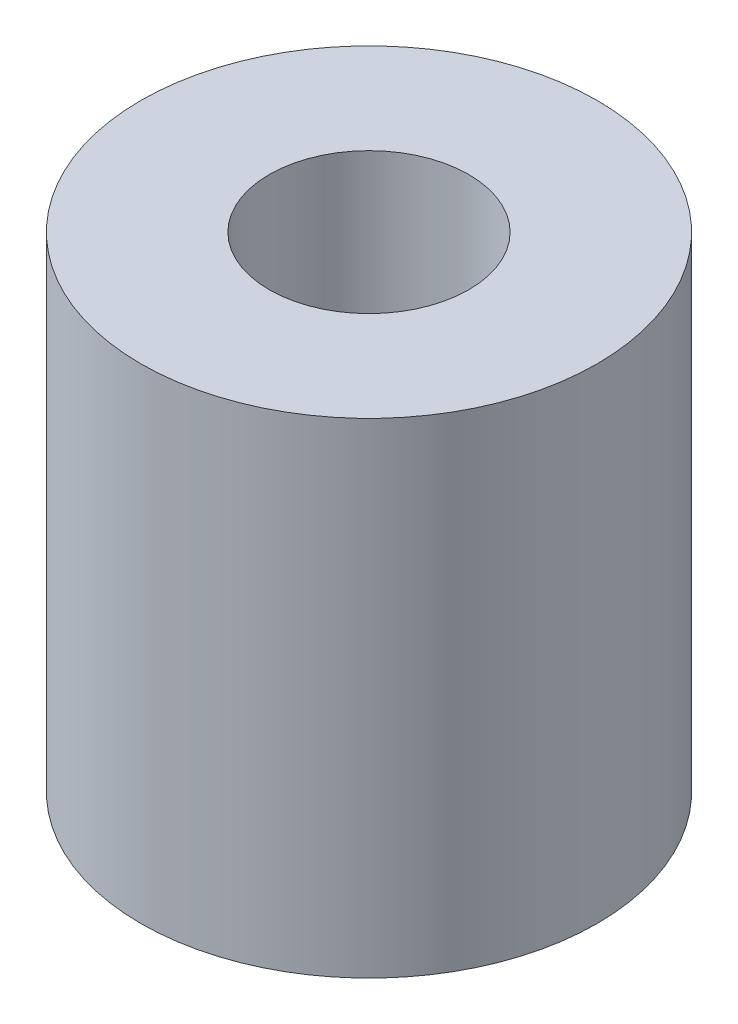
SolidWorks part; units mm, degrees
ref_plane "Спереди" through (0, 0, 0) normal (0, 0, 1) x (1, 0, 0)
ref_plane "Сверху" through (0, 0, 0) normal (0, 1, 0) x (1, 0, 0)
ref_plane "Справа" through (0, 0, 0) normal (1, 0, 0) x (0, 0, -1)
sketch "Эскиз1" plane through (0, 0, 0) normal (0, 1, 0) x (1, 0, 0)
  circle A0 centre (0, 0) radius 4
  circle A1 centre (0, 0) radius 1.75
  dimension "D1" = 8
  dimension "D2" = 3.5
extrude "Бобышка-Вытянуть1" add sketch "Эскиз1" along normal blind 8.5
